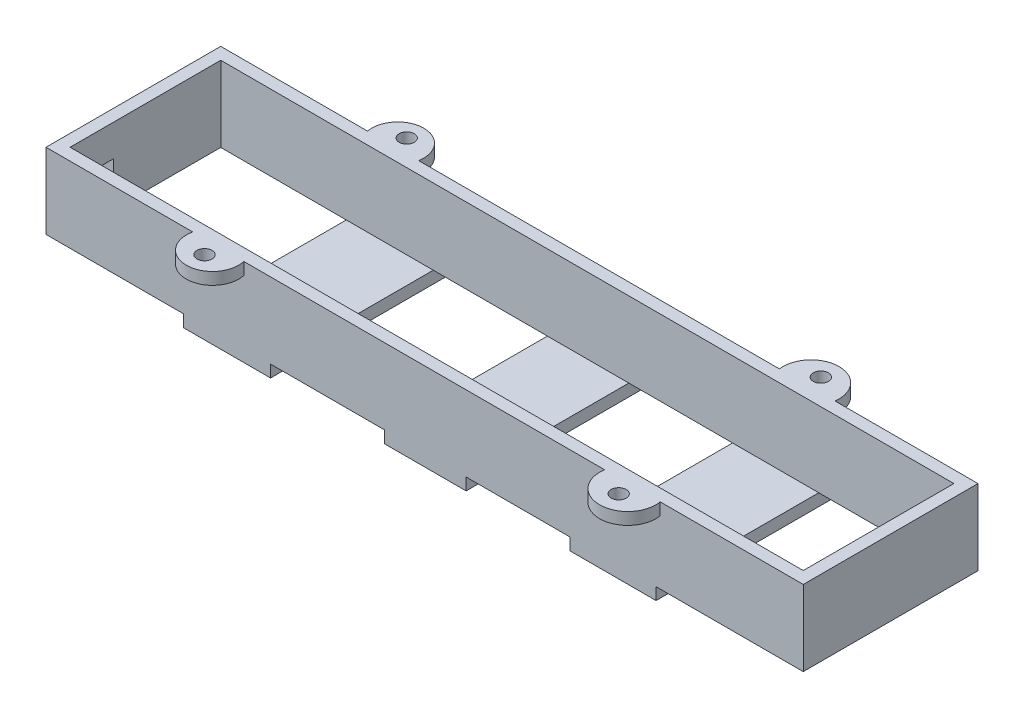
SolidWorks part; units mm, degrees
ref_plane "Front Plane" through (0, 0, 0) normal (0, 0, 1) x (1, 0, 0)
ref_plane "Top Plane" through (0, 0, 0) normal (0, 1, 0) x (1, 0, 0)
ref_plane "Right Plane" through (0, 0, 0) normal (1, 0, 0) x (0, 0, -1)
sketch "Sketch1" plane through (0, 0, 0) normal (0, 1, 0) x (1, 0, 0)
  line L0 (-56.8148, 13.6159) -> (182.5802, 13.6159)
  line L1 (-53.0048, 9.8059) -> (178.7702, 9.8059)
  line L2 (-53.0048, 9.8059) -> (-53.0048, -37.8191)
  line L3 (-53.0048, -37.8191) -> (178.7702, -37.8191)
  line L4 (178.7702, 9.8059) -> (178.7702, -37.8191)
  line L5 (182.5802, 13.6159) -> (182.5802, -41.6291)
  line L6 (-56.8148, -41.6291) -> (182.5802, -41.6291)
  line L7 (-56.8148, 13.6159) -> (-56.8148, -41.6291)
  dimension "D1" = 231.775
  dimension "D2" = 47.625
  dimension "D3" = 3.81
extrude "Boss-Extrude1" add sketch "Sketch1" along normal blind 23.876
sketch "Sketch2" plane through (0, 0, 0) normal (0, -1, 0) x (1, 0, 0)
  line L1 (-13.3143, 41.6291) -> (14.1873, 41.6291)
  line L2 (-13.3143, 41.6291) -> (-13.3143, -13.6159)
  line L3 (-13.3143, -13.6159) -> (14.1873, -13.6159)
  line L4 (14.1873, 41.6291) -> (14.1873, -13.6159)
  line L5 (108.8028, 41.6291) -> (136.0521, 41.6291)
  line L6 (108.8028, 41.6291) -> (108.8028, -13.6159)
  line L7 (108.8028, -13.6159) -> (136.0521, -13.6159)
  line L8 (136.0521, 41.6291) -> (136.0521, -13.6159)
  line L9 (50.2673, 41.6291) -> (76.0028, 41.6291)
  line L10 (50.2673, 41.6291) -> (50.2673, -13.6159)
  line L11 (50.2673, -13.6159) -> (76.0028, -13.6159)
  line L12 (76.0028, 41.6291) -> (76.0028, -13.6159)
  line M2 (-56.8148, -13.6159) -> (182.5802, -13.6159)
  line M4 (182.5802, 41.6291) -> (-56.8148, 41.6291)
  line M6 (-53.0048, 37.8191) -> (178.7702, 37.8191)
  line M8 (178.7702, -9.8059) -> (-53.0048, -9.8059)
extrude "Boss-Extrude2" add sketch "Sketch2" along normal blind 3.81 contours L4 L2 M6 M8 | L8 L6 M6 M8 | L8 L6 M4 M6 | L4 L2 M4 M6 | L4 L2 M8 M2 | L8 L6 M8 M2 | L9 L12 L11 L10
sketch "Sketch3" plane through (-56.8148, 0, 0) normal (-1, 0, 0) x (0, 0, 1)
  line L1 (24.1386, 13.8588) -> (37.0459, 13.8588)
  line L2 (24.1386, 13.8588) -> (24.1386, 0)
  line L3 (24.1386, 0) -> (37.0459, 0)
  line L4 (37.0459, 13.8588) -> (37.0459, 0)
extrude "Cut-Extrude1" cut sketch "Sketch3" against normal blind 3.81
ref_plane "Plane1" through (0, 23.876, 0) normal (0, 1, 0) x (1, 0, 0)
sketch "Sketch4" plane through (0, 23.876, 0) normal (0, 1, 0) x (1, 0, 0)
  line L0 (-2.4512, 13.6159) -> (-2.4512, -41.6291) construction
  line L1 (128.5875, 14.8312) -> (128.5875, -41.6291) construction
  line L2 (-10.4121, 13.6159) -> (5.7433, 13.6159)
  line L3 (-10.4121, -41.6291) -> (5.7433, -41.6291)
  line L4 (119.8051, -41.6291) -> (137.3699, -41.6291)
  line L5 (119.8051, 13.6159) -> (137.3699, 13.6159)
  arc A0 (-10.4121, 13.6159) -> (5.7433, 13.6159) centre (-2.3344, 15.1016) cw
  arc A1 (-10.4121, -41.6291) -> (5.7433, -41.6291) centre (-2.3344, -43.4619) ccw
  arc A2 (119.8051, 13.6159) -> (137.3699, 13.6159) centre (128.5875, 14.8312) cw
  arc A3 (119.8051, -41.6291) -> (137.3699, -41.6291) centre (128.5875, -43.1063) ccw
  circle A4 centre (-2.3344, 17.9178) radius 2.3813
  circle A5 centre (-2.3344, -45.992) radius 2.3812
  circle A6 centre (128.5875, 17.9178) radius 2.3813
  circle A7 centre (128.5875, -45.992) radius 2.3813
  dimension "D1" = 4.7625
  dimension "D2" = 4.7625
  dimension "D3" = 4.7625
  dimension "D4" = 4.7625
extrude "Boss-Extrude3" add sketch "Sketch4" against normal blind 3.81
